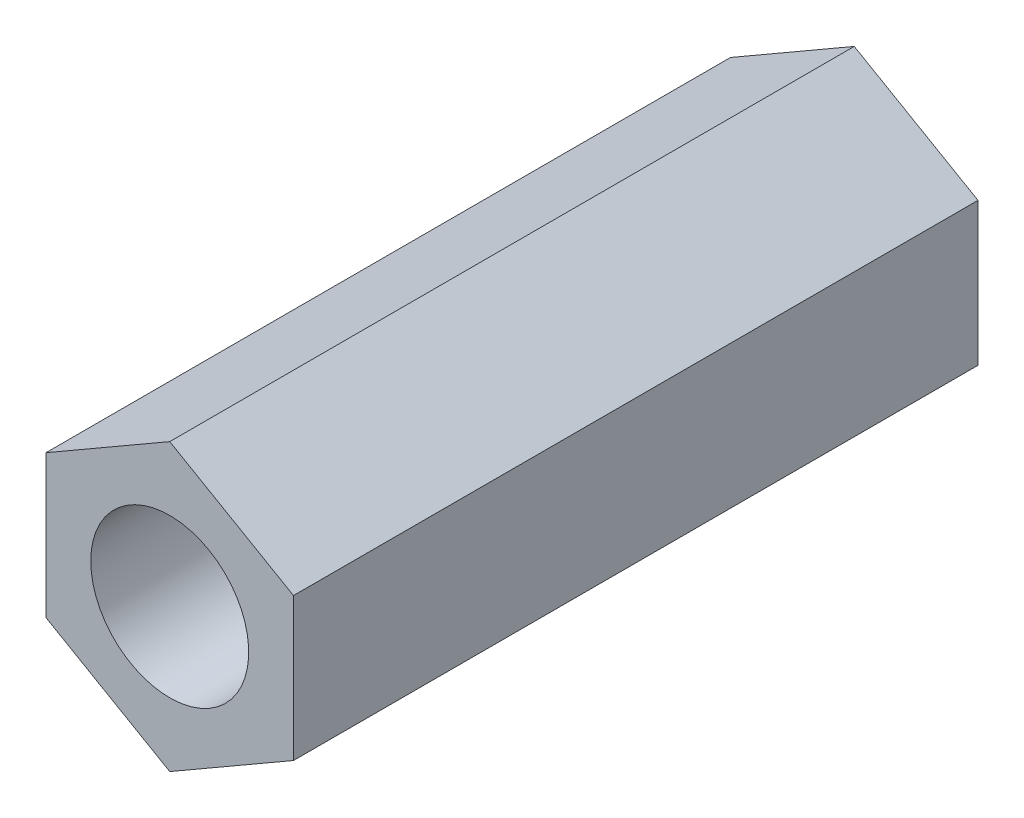
SolidWorks part; units mm, degrees
ref_plane "前视基准面" through (0, 0, 0) normal (0, 0, 1) x (1, 0, 0)
ref_plane "上视基准面" through (0, 0, 0) normal (0, 1, 0) x (1, 0, 0)
ref_plane "右视基准面" through (0, 0, 0) normal (1, 0, 0) x (0, 0, -1)
sketch "草图1" plane through (0, 0, 0) normal (0, 0, 1) x (1, 0, 0)
  line L1 (2.35, -1.3568) -> (2.35, 1.3568)
  line L2 (2.35, 1.3568) -> (0, 2.7135)
  line L3 (0, 2.7135) -> (-2.35, 1.3568)
  line L4 (-2.35, 1.3568) -> (-2.35, -1.3568)
  line L5 (-2.35, -1.3568) -> (0, -2.7135)
  line L6 (0, -2.7135) -> (2.35, -1.3568)
  circle A0 centre (0, 0) radius 2.35 construction
  circle A1 centre (0, 0) radius 1.5
  dimension "D2" = 3
  dimension "D1" = 4.7
extrude "凸台-拉伸1" add sketch "草图1" along normal blind 13
